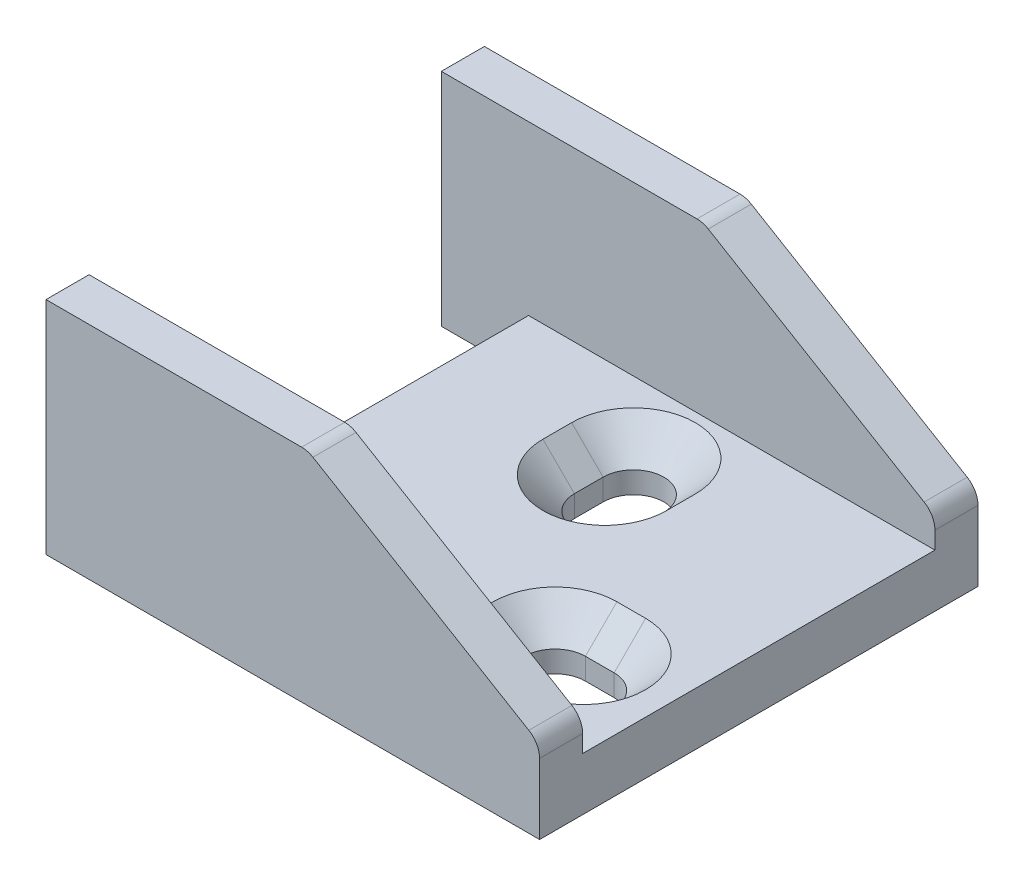
SolidWorks part; units mm, degrees
ref_plane "Front Plane" through (0, 0, 0) normal (0, 0, 1) x (1, 0, 0)
ref_plane "Top Plane" through (0, 0, 0) normal (0, 1, 0) x (1, 0, 0)
ref_plane "Right Plane" through (0, 0, 0) normal (1, 0, 0) x (0, 0, -1)
sketch "Sketch1" plane through (0, 0, 0) normal (0, 1, 0) x (1, 0, 0)
  line L1 (0, 0) -> (36.8, 0)
  line L2 (0, 0) -> (0, 39.7)
  line L3 (0, 39.7) -> (36.8, 39.7)
  line L4 (36.8, 0) -> (36.8, 39.7)
  dimension "D1" = 36.8
  dimension "D2" = 39.7
extrude "Boss-Extrude1" add sketch "Sketch1" along normal blind 4.8
sketch "Sketch2" plane through (0, 0, 0) normal (0, 1, 0) x (1, 0, 0)
  line L0 (36.8, 19.85) -> (0, 19.85) construction
  line L1 (36.8, 39.7) -> (-7.9, 39.7)
  line L2 (36.8, 39.7) -> (36.8, 35.8)
  line L3 (36.8, 35.8) -> (-7.9, 35.8)
  line L4 (-7.9, 39.7) -> (-7.9, 35.8)
  line L5 (36.8, 0) -> (36.8, 39.7) construction
  line L6 (0, 39.7) -> (0, 0) construction
  line L7 (36.8, 0) -> (36.8, 3.9)
  line L8 (-7.9, 0) -> (-7.9, 3.9)
  line L9 (36.8, 0) -> (-7.9, 0)
  line L10 (36.8, 3.9) -> (-7.9, 3.9)
  dimension "D1" = 3.9
  dimension "D2" = 44.7
extrude "Boss-Extrude2" add sketch "Sketch2" along normal blind 20
sketch "Sketch3" plane through (0, 4.8, 0) normal (0, 1, 0) x (1, 0, 0)
  line L0 (26.45, 11.75) -> (29.05, 11.75) construction
  line L1 (26.45, 14.5) -> (29.05, 14.5)
  line L2 (26.45, 9) -> (29.05, 9)
  line L3 (15.95, 29.35) -> (15.95, 26.75) construction
  line L4 (18.7, 29.35) -> (18.7, 26.75)
  line L5 (13.2, 29.35) -> (13.2, 26.75)
  line L6 (-7.9, 0) -> (36.8, 0) construction
  line L7 (36.8, 3.9) -> (36.8, 35.8) construction
  arc A0 (26.45, 14.5) -> (26.45, 9) centre (26.45, 11.75) ccw
  arc A1 (29.05, 9) -> (29.05, 14.5) centre (29.05, 11.75) ccw
  arc A2 (18.7, 29.35) -> (13.2, 29.35) centre (15.95, 29.35) ccw
  arc A3 (13.2, 26.75) -> (18.7, 26.75) centre (15.95, 26.75) ccw
  point P2 (27.75, 11.75)
  point P9 (15.95, 28.05)
  point P14 (27.75, 9)
  dimension "D3" = 8.1
  dimension "D4" = 8.1
  dimension "D1" = 5.5
  dimension "D2" = 5.5
  dimension "D5" = 9
  dimension "D6" = 5
  dimension "D7" = 18.1
  dimension "D8" = 24
extrude "Cut-Extrude1" cut sketch "Sketch3" against normal up to next
chamfer "Chamfer1" distance 2.85 angle 45 8 edges at (23.7, 4.8, -11.75) (27.75, 4.8, -9) (31.8, 4.8, -11.75) (27.75, 4.8, -14.5) (13.2, 4.8, -28.05) (15.95, 4.8, -24) (18.7, 4.8, -28.05) (15.95, 4.8, -32.1)
sketch "Sketch4" plane through (0, 0, -39.7) normal (0, 0, -1) x (-1, 0, 0)
  line L0 (-36.8, 20) -> (-36.8, 7.5)
  line L1 (-36.8, 20) -> (-36.8, 0) construction
  line L2 (-36.8, 7.5) -> (-15.8, 20)
  line L3 (-36.8, 20) -> (7.9, 20) construction
  line L4 (-15.8, 20) -> (-36.8, 20)
  dimension "D1" = 7.5
  dimension "D2" = 21
extrude "Cut-Extrude2" cut sketch "Sketch4" against normal through all
fillet "Fillet1" radius 2 4 edges at (36.8, 7.5, -1.95) (36.8, 7.5, -37.75) (15.8, 20, -37.75) (15.8, 20, -1.95)
